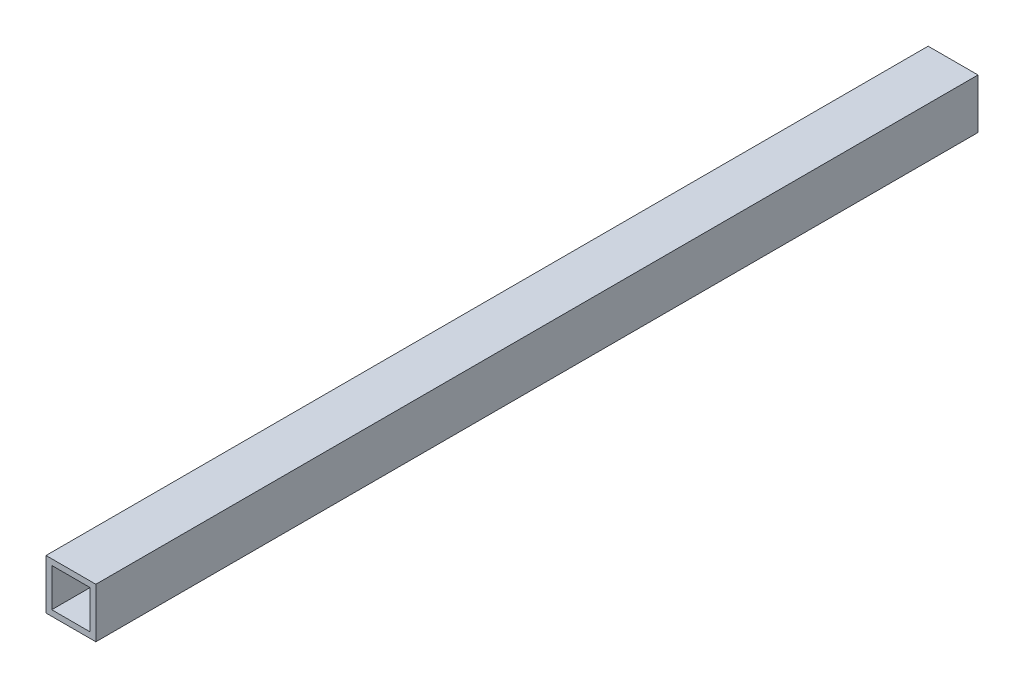
SolidWorks part; units mm, degrees
ref_plane "Front Plane" through (0, 0, 0) normal (0, 0, 1) x (1, 0, 0)
ref_plane "Top Plane" through (0, 0, 0) normal (0, 1, 0) x (1, 0, 0)
ref_plane "Right Plane" through (0, 0, 0) normal (1, 0, 0) x (0, 0, -1)
sketch "Sketch1" plane through (0, 0, 0) normal (0, 0, 1) x (1, 0, 0)
  line L1 (-6.5, 6.5) -> (6.5, 6.5)
  line L2 (-6.5, 6.5) -> (-6.5, -6.5)
  line L3 (-6.5, -6.5) -> (6.5, -6.5)
  line L4 (6.5, 6.5) -> (6.5, -6.5)
  line L5 (-6.5, 6.5) -> (6.5, -6.5) construction
  line L6 (-6.5, -6.5) -> (6.5, 6.5) construction
  line L7 (-5, -5) -> (5, -5)
  line L8 (-5, -5) -> (-5, 5)
  line L9 (-5, 5) -> (5, 5)
  line L10 (5, -5) -> (5, 5)
  line L11 (-5, -5) -> (5, 5) construction
  line L12 (-5, 5) -> (5, -5) construction
  point P0 (0, 0)
  point P6 (0, 0)
  dimension "D1" = 13
  dimension "D2" = 13
  dimension "D3" = 1.5
extrude "Boss-Extrude1" add sketch "Sketch1" along normal blind 230
